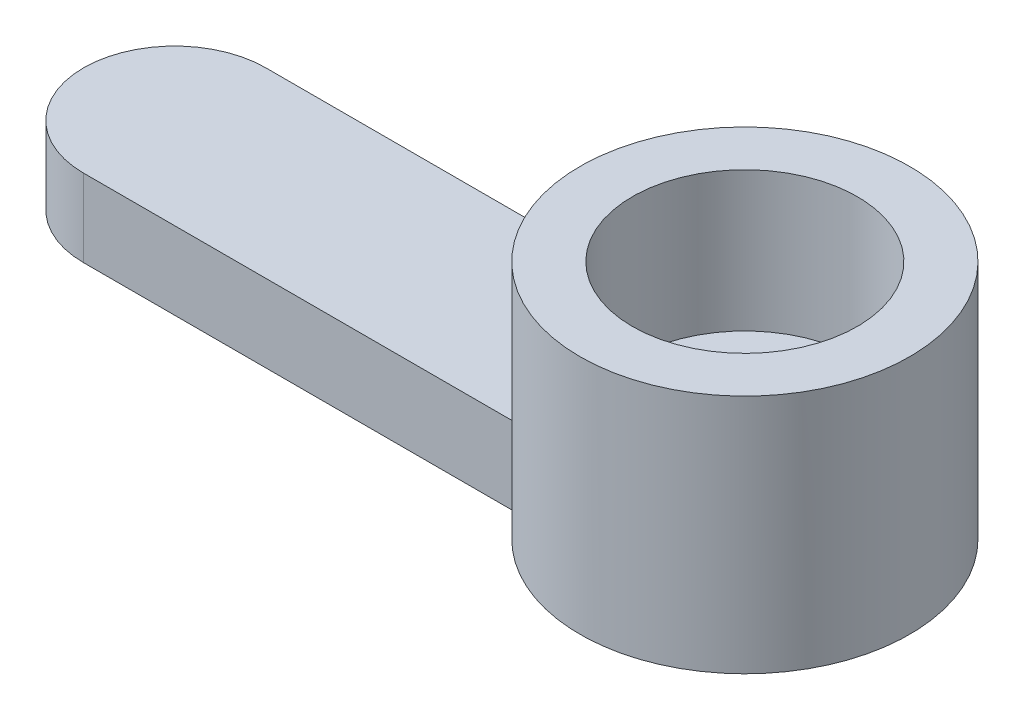
SolidWorks part; units mm, degrees
ref_plane "Front Plane" through (0, 0, 0) normal (0, 0, 1) x (1, 0, 0)
ref_plane "Top Plane" through (0, 0, 0) normal (0, 1, 0) x (1, 0, 0)
ref_plane "Right Plane" through (0, 0, 0) normal (1, 0, 0) x (0, 0, -1)
sketch "Sketch1" plane through (0, 0, 0) normal (0, 1, 0) x (1, 0, 0)
  circle A0 centre (0, 0) radius 2.125
  dimension "D1" = 4.25
extrude "Boss-Extrude1" add sketch "Sketch1" along normal blind 3.1
sketch "Sketch2" plane through (0, 3.1, 0) normal (0, 1, 0) x (1, 0, 0)
  circle A0 centre (0, 0) radius 1.45
  dimension "D1" = 2.9
extrude "Cut-Extrude1" cut sketch "Sketch2" against normal blind 1.8
sketch "Sketch3" plane through (0, 1.3, 0) normal (0, 1, 0) x (1, 0, 0)
  circle A0 centre (0, 0) radius 0.8
  dimension "D1" = 1.6
extrude "Cut-Extrude2" cut sketch "Sketch3" against normal blind 0.65 contours A0
sketch "Sketch4" plane through (0, 0, 0) normal (0, 1, 0) x (1, 0, 0)
  line L0 (-1.7706, -1.175) -> (-7.35, -1.175)
  line L1 (-1.7706, 1.175) -> (-7.35, 1.175)
  circle A0 centre (0, 0) radius 2.125 construction
  circle A1 centre (0, 0) radius 2.125 construction
  arc A2 (-7.35, -1.175) -> (-7.35, 1.175) centre (-7.35, 0) cw
  arc A3 (-1.7706, -1.175) -> (-1.7706, 1.175) centre (0, 0) cw
  point P5 (0, 0)
  point P9 (0, 0)
  dimension "D2" = 7.35
  dimension "D1" = 2.35
extrude "Boss-Extrude3" add sketch "Sketch4" along normal blind 1 contours L0 A2 L1 A3
